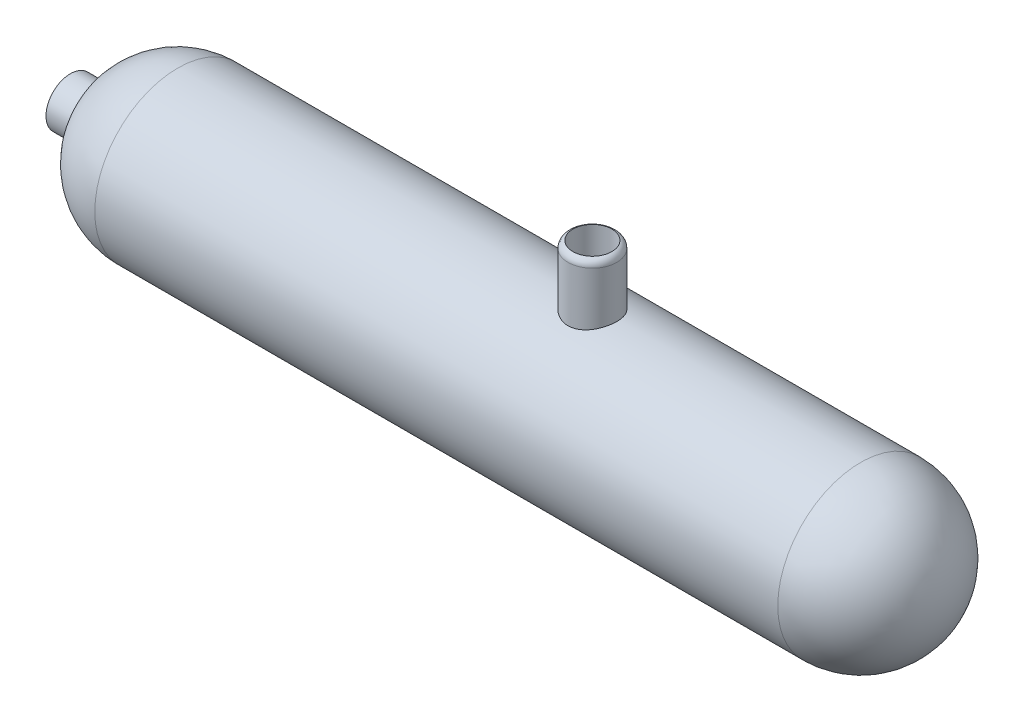
SolidWorks part; units mm, degrees
ref_plane "Front Plane" through (0, 0, 0) normal (0, 0, 1) x (1, 0, 0)
ref_plane "Top Plane" through (0, 0, 0) normal (0, 1, 0) x (1, 0, 0)
ref_plane "Right Plane" through (0, 0, 0) normal (1, 0, 0) x (0, 0, -1)
sketch "Sketch2" plane through (0, 0, 0) normal (0, 0, 1) x (1, 0, 0)
  line L1 (-7000, 1700) -> (7000, 1700)
  line L2 (-8700, 0) -> (-7000, 0)
  line L4 (-7000, 0) -> (-7000, 1500)
  line L5 (-7000, 1500) -> (7000, 1500)
  line L6 (7000, 0) -> (7000, 1500)
  line L7 (7000, 0) -> (8700, 0)
  line L8 (-7000, 0) -> (7000, 0) construction
  arc A2 (-7000, 1700) -> (-8700, 0) centre (-7000, 0) ccw
  arc A3 (7000, 1700) -> (8700, 0) centre (7000, 0) cw
  dimension "D1" = 14000
  dimension "D2" = 1700
  dimension "D3" = 1500
revolve "Revolve2" add sketch "Sketch2" angle 360 about L8
ref_plane "Plane1" through (0, 1700, 0) normal (0, 1, 0) x (1, 0, 0)
sketch "Sketch3" plane through (0, 1700, 0) normal (0, 1, 0) x (1, 0, 0)
  circle A0 centre (1500, 0) radius 500
  dimension "D1" = 1000
extrude "Boss-Extrude1" add sketch "Sketch3" along normal blind 1200 and the other way blind 100 contours A0
fillet "Fillet1" radius 150 1 edges at (1500, 2900, 500)
ref_plane "Plane2" through (-3250, 0, 0) normal (1, 0, 0) x (0, 0, -1)
ref_plane "Plane3" through (-1750, 0, 0) normal (1, 0, 0) x (0, 0, -1)
ref_plane "Plane4" through (-4500, 0, 0) normal (1, 0, 0) x (0, 0, -1)
ref_plane "Plane5" through (4864.908, 0, 0) normal (1, 0, 0) x (0, 0, -1)
sketch "Sketch4" plane through (-3250, 0, 0) normal (1, 0, 0) x (0, 0, -1)
  circle A0 centre (0, 0) radius 1500
  dimension "D1" = 3000
sketch "Sketch5" plane through (-1750, 0, 0) normal (1, 0, 0) x (0, 0, -1)
  circle A0 centre (0, 0) radius 1500
sketch "Sketch6" plane through (-4500, 0, 0) normal (1, 0, 0) x (0, 0, -1)
  circle A0 centre (0, 0) radius 1500
sketch "Sketch7" plane through (4864.908, 0, 0) normal (1, 0, 0) x (0, 0, -1)
  circle A0 centre (0, 0) radius 1500
extrude "Boss-Extrude3" add sketch "Sketch4" along normal mid plane 200
extrude "Boss-Extrude4" add sketch "Sketch5" along normal mid plane 200
extrude "Boss-Extrude5" add sketch "Sketch6" along normal mid plane 200
extrude "Boss-Extrude6" add sketch "Sketch7" along normal mid plane 200
ref_plane "Plane6" through (-8700, 0, 0) normal (-1, 0, 0) x (0, 0, 1)
sketch "Sketch11" plane through (-8700, 0, 0) normal (-1, 0, 0) x (0, 0, 1)
  circle A0 centre (0, 0) radius 500
  dimension "D1" = 1000
extrude "Boss-Extrude7" add sketch "Sketch11" along normal blind 500 and the other way blind 120 contours A0
sketch "Sketch12" plane through (0, 2900, 0) normal (0, 1, 0) x (1, 0, 0)
  circle A0 centre (1500, 0) radius 400
  dimension "D1" = 800
extrude "Cut-Extrude1" cut sketch "Sketch12" against normal blind 1746
